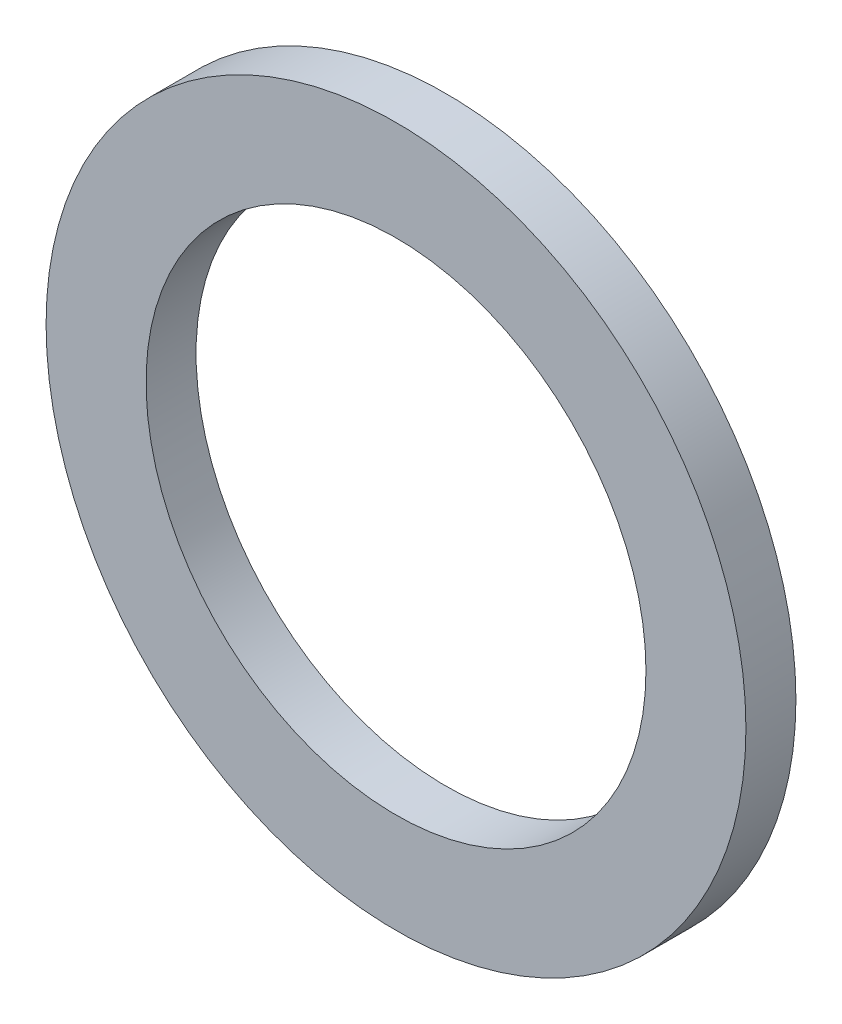
SolidWorks part; units mm, degrees
ref_plane "정면" through (0, 0, 0) normal (0, 0, 1) x (1, 0, 0)
ref_plane "윗면" through (0, 0, 0) normal (0, 1, 0) x (1, 0, 0)
ref_plane "우측면" through (0, 0, 0) normal (1, 0, 0) x (0, 0, -1)
sketch "스케치1" plane through (0, 0, 0) normal (0, 0, 1) x (1, 0, 0)
  circle A0 centre (0, 0) radius 2.5
  circle A1 centre (0, 0) radius 3.5
  dimension "D1" = 5
  dimension "D2" = 7
extrude "보스-돌출1" add sketch "스케치1" along normal blind 0.5 contours A0
